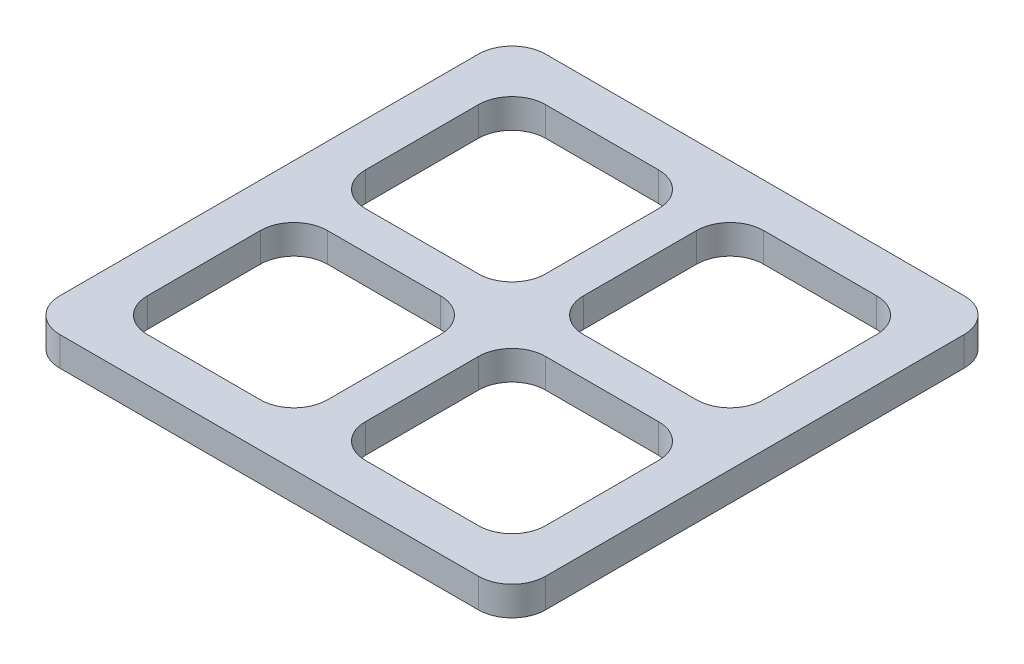
SolidWorks part; units mm, degrees
ref_plane "Front Plane" through (0, 0, 0) normal (0, 0, 1) x (1, 0, 0)
ref_plane "Top Plane" through (0, 0, 0) normal (0, 1, 0) x (1, 0, 0)
ref_plane "Right Plane" through (0, 0, 0) normal (1, 0, 0) x (0, 0, -1)
sketch "Sketch1" plane through (0, 0, 0) normal (0, 1, 0) x (1, 0, 0)
  line L0 (-8.325, -8.325) -> (8.325, 8.325) construction
  line L1 (-8.325, -8.325) -> (8.325, -8.325)
  line L2 (-8.325, -8.325) -> (-8.325, 8.325)
  line L3 (-8.325, 8.325) -> (8.325, 8.325)
  line L4 (8.325, -8.325) -> (8.325, 8.325)
  line L5 (8.325, -8.325) -> (-8.325, 8.325) construction
  line L7 (-6.825, 6.825) -> (6.825, 6.825)
  line L8 (-6.825, 6.825) -> (-6.825, -6.825)
  line L9 (-6.825, -6.825) -> (6.825, -6.825)
  line L10 (6.825, 6.825) -> (6.825, -6.825)
  line L11 (-6.825, 6.825) -> (6.825, -6.825) construction
  line L12 (-6.825, -6.825) -> (6.825, 6.825) construction
  line L13 (-0.65, 6.825) -> (0.65, 6.825)
  line L14 (-0.65, 6.825) -> (-0.65, -6.825)
  line L15 (-0.65, -6.825) -> (0.65, -6.825)
  line L16 (0.65, 6.825) -> (0.65, -6.825)
  line L17 (-0.65, 6.825) -> (0.65, -6.825) construction
  line L18 (-0.65, -6.825) -> (0.65, 6.825) construction
  line L19 (-6.825, 0.65) -> (6.825, 0.65)
  line L20 (-6.825, 0.65) -> (-6.825, -0.65)
  line L21 (-6.825, -0.65) -> (6.825, -0.65)
  line L22 (6.825, 0.65) -> (6.825, -0.65)
  line L23 (-6.825, 0.65) -> (6.825, -0.65) construction
  line L24 (-6.825, -0.65) -> (6.825, 0.65) construction
  point P0 (0, 0)
  point P6 (0, 0)
  point P7 (0, 0)
  point P12 (0, 0)
  point P17 (0, 0)
  point P26 (0, 0)
  dimension "D1" = 13.65
  dimension "D2" = 16.65
  dimension "D3" = 1.3
  dimension "D4" = 1.3
extrude "Boss-Extrude1" add sketch "Sketch1" along normal blind 1 contours L1 L4 L3 L2 L7 L10 L9 L8 | L8 L21 L14 L19 | L14 L21 L16 L19 | L21 L14 L9 L16 | L16 L21 L10 L19 | L14 L19 L16 L7
fillet "Fillet1" radius 1.15 20 edges at (-6.825, 0.5, 6.825) (-8.325, 0.5, 8.325) (0.65, 0.5, -0.65) (0.65, 0.5, 6.825) (-6.825, 0.5, 0.65) (0.65, 0.5, -6.825) (0.65, 0.5, 0.65) (6.825, 0.5, 0.65) (-0.65, 0.5, -6.825) (6.825, 0.5, -6.825) (-0.65, 0.5, 0.65) (6.825, 0.5, -0.65) (6.825, 0.5, 6.825) (-8.325, 0.5, -8.325) (8.325, 0.5, -8.325) (8.325, 0.5, 8.325) (-6.825, 0.5, -0.65) (-6.825, 0.5, -6.825) (-0.65, 0.5, 6.825) (-0.65, 0.5, -0.65)
